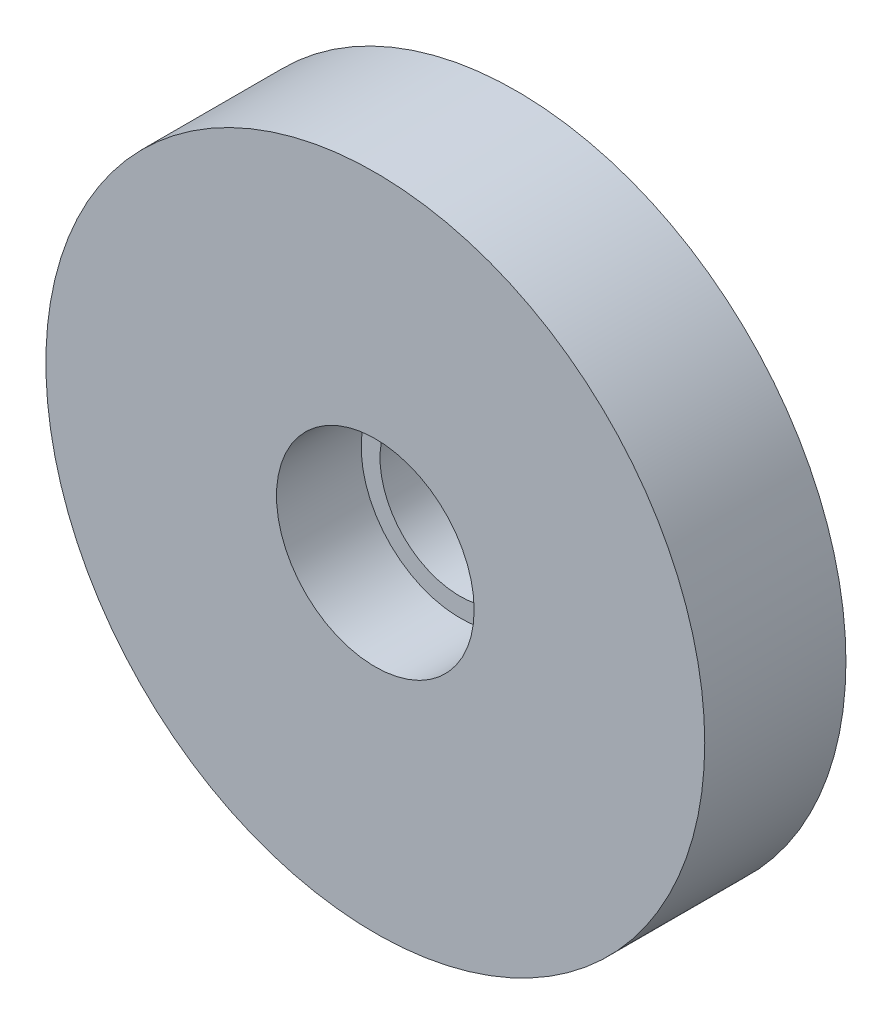
SolidWorks part; units mm, degrees
ref_plane "Plan de face" through (0, 0, 0) normal (0, 0, 1) x (1, 0, 0)
ref_plane "Plan de dessus" through (0, 0, 0) normal (0, 1, 0) x (1, 0, 0)
ref_plane "Plan de droite" through (0, 0, 0) normal (1, 0, 0) x (0, 0, -1)
sketch "Esquisse1" plane through (0, 0, 0) normal (0, 0, 1) x (1, 0, 0)
  circle A0 centre (0, 0) radius 8.5
  circle A1 centre (0, 0) radius 35
  dimension "D1" = 17
  dimension "D2" = 70
extrude "Boss.-Extru.1" add sketch "Esquisse1" along normal blind 15
sketch "Esquisse2" plane through (0, 0, 15) normal (0, 0, 1) x (1, 0, 0)
  circle A0 centre (0, 0) radius 10.5
  dimension "D1" = 21
extrude "Enlèv. mat.-Extru.1" cut sketch "Esquisse2" against normal blind 9
sketch "Esquisse3" plane through (0, 0, 15) normal (0, 0, 1) x (1, 0, 0)
  line L0 (0, 35) -> (0, -35) construction
  circle A0 centre (0, 0) radius 35 construction
